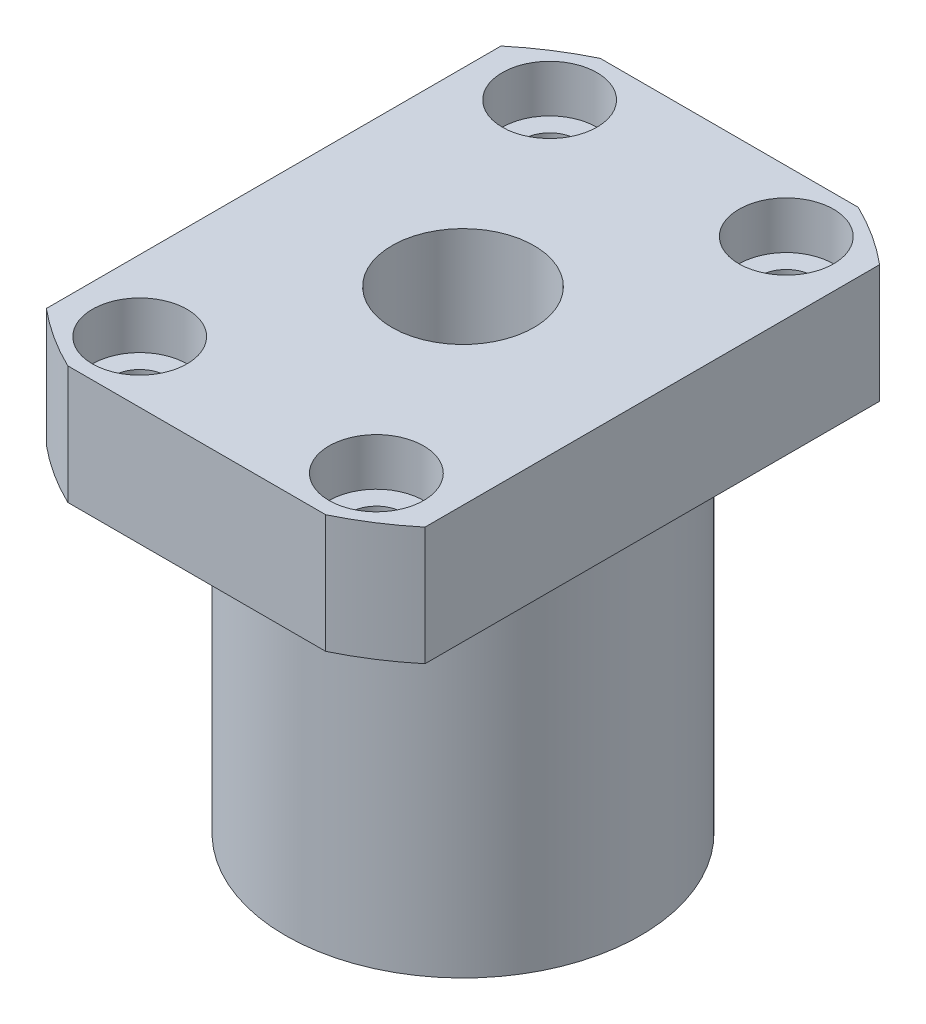
SolidWorks part; units mm, degrees
ref_plane "정면" through (0, 0, 0) normal (0, 0, 1) x (1, 0, 0)
ref_plane "윗면" through (0, 0, 0) normal (0, 1, 0) x (1, 0, 0)
ref_plane "우측면" through (0, 0, 0) normal (1, 0, 0) x (0, 0, -1)
sketch "스케치1" plane through (0, 0, 0) normal (0, 1, 0) x (1, 0, 0)
  circle A0 centre (0, 0) radius 15
  dimension "D1" = 30
extrude "보스-돌출1" add sketch "스케치1" along normal blind 30
sketch "스케치2" plane through (0, 30, 0) normal (0, 1, 0) x (1, 0, 0)
  line L1 (-16, -22.5) -> (16, -22.5)
  line L2 (-16, -22.5) -> (-16, 22.5)
  line L3 (-16, 22.5) -> (16, 22.5)
  line L4 (16, -22.5) -> (16, 22.5)
  line L5 (-16, -22.5) -> (16, 22.5) construction
  line L6 (-16, 22.5) -> (16, -22.5) construction
  point P0 (0, 0)
  dimension "D1" = 45
  dimension "D2" = 32
extrude "보스-돌출2" add sketch "스케치2" along normal blind 10
sketch "스케치3" plane through (0, 40, 0) normal (0, 1, 0) x (1, 0, 0)
  line L0 (0, 20) -> (0, -20) construction
  line L1 (-10, 17.3205) -> (10, -17.3205) construction
  line L2 (10, 17.3205) -> (-10, -17.3205) construction
  circle A0 centre (0, 0) radius 20 construction
  dimension "D1" = 40
  dimension "D2" = 30
  dimension "D3" = 30
hole_wizard "M4 소켓 머리 캡 나사용 카운터보어1" positions "스케치5" profile "스케치4" counterbore size "M4" standard "KS" end condition through all
sketch "스케치5" plane through (0, 40, 0) normal (0, 1, 0) x (1, 0, 0)
  point P0 (-10, 17.3205)
  point P3 (10, 17.3205)
  point P6 (10, -17.3205)
  point P9 (-10, -17.3205)
sketch "스케치4" plane through (-10, 40, -17.3205) normal (1, 0, 0) x (0, 0, 1)
  line L0 (0, 0) -> (0, 40)
  line L1 (0, 40) -> (2.25, 40)
  line L3 (2.25, 40) -> (2.25, 4)
  line L4 (2.25, 4) -> (4, 4)
  line L5 (4, 4) -> (4, 0)
  line L7 (4, 0) -> (0, 0)
  line L11 (0, -6.35) -> (0, 107.95) construction
  dimension "관통 구멍 지름" = 4.5
  dimension "관통 구멍 깊이" = 40
  dimension "카운터보어 지름" = 8
  dimension "카운터보어 깊이" = 4
sketch "스케치6" plane through (0, 40, 0) normal (0, 1, 0) x (1, 0, 0)
  line L1 (39.4951, -31.4184) -> (-39.4951, -31.4184)
  line L2 (39.4951, -31.4184) -> (39.4951, 31.4184)
  line L3 (39.4951, 31.4184) -> (-39.4951, 31.4184)
  line L4 (-39.4951, -31.4184) -> (-39.4951, 31.4184)
  line L5 (39.4951, -31.4184) -> (-39.4951, 31.4184) construction
  line L6 (39.4951, 31.4184) -> (-39.4951, -31.4184) construction
  circle A0 centre (0, 0) radius 25
extrude "컷-돌출1" cut sketch "스케치6" against normal blind 30
sketch "스케치7" plane through (0, 40, 0) normal (0, 1, 0) x (1, 0, 0)
  circle A0 centre (0, 0) radius 6
extrude "컷-돌출2" cut sketch "스케치7" against normal through all
